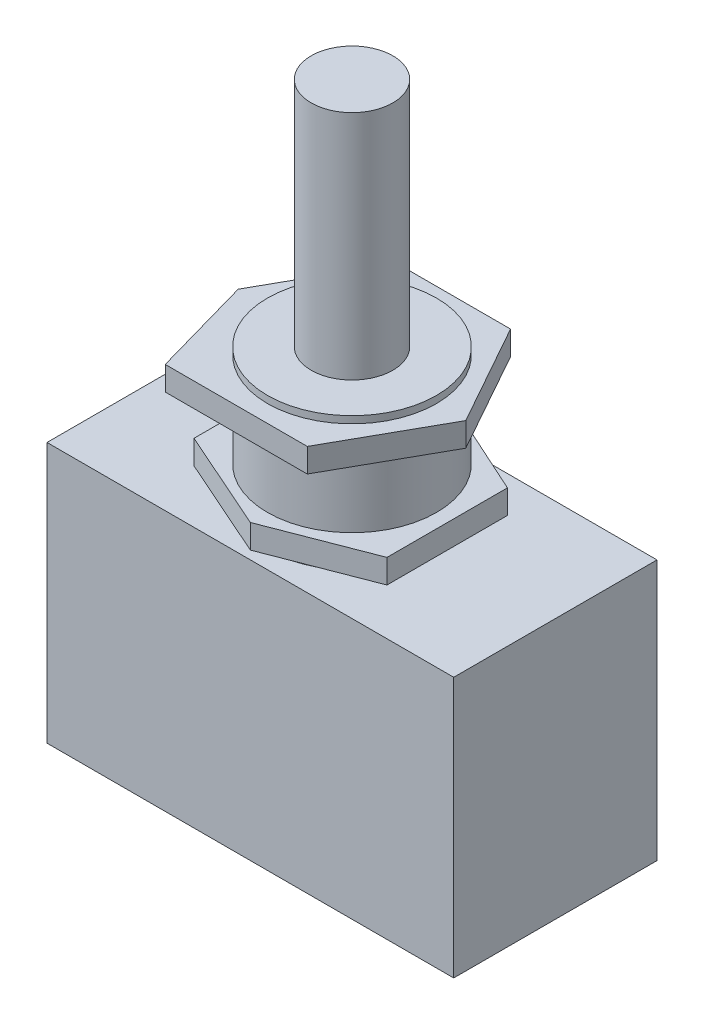
SolidWorks part; units mm, degrees
ref_plane "Front Plane" through (0, 0, 0) normal (0, 0, 1) x (1, 0, 0)
ref_plane "Top Plane" through (0, 0, 0) normal (0, 1, 0) x (1, 0, 0)
ref_plane "Right Plane" through (0, 0, 0) normal (1, 0, 0) x (0, 0, -1)
other "Configuration Table"
sketch "BodyProfile" plane through (0, 0, 0) normal (0, 0, 1) x (1, 0, 0)
  line L1 (-14.445, -9.25) -> (14.445, -9.25)
  line L2 (-14.445, -9.25) -> (-14.445, 9.25)
  line L3 (-14.445, 9.25) -> (14.445, 9.25)
  line L4 (14.445, -9.25) -> (14.445, 9.25)
  line L5 (-14.445, -9.25) -> (14.445, 9.25) construction
  line L6 (-14.445, 9.25) -> (14.445, -9.25) construction
  point P0 (0, 0)
extrude "BodyBoss" add sketch "BodyProfile" along normal mid plane 14.44
ref_plane "TopOfBodyPlane" through (0, 9.25, 0) normal (0, 1, 0) x (1, 0, 0)
ref_plane "BottomOfBodyPlane" through (0, 0, 0) normal (0, 1, 0) x (1, 0, 0)
sketch "BushingStemProfile" plane through (0, 9.25, 0) normal (0, 1, 0) x (1, 0, 0)
  circle A0 centre (0, 0) radius 6
extrude "BushingStem" add sketch "BushingStemProfile" along normal blind 9.5
sketch "WasherProfile" plane through (0, 9.25, 0) normal (0, 1, 0) x (1, 0, 0)
  circle A0 centre (0, 0) radius 6
extrude "WasherBoss" add sketch "WasherProfile" along normal blind 0.6
ref_plane "LowerNutPlane" through (0, 9.85, 0) normal (0, 1, 0) x (1, 0, 0)
sketch "LowerNutProfile" plane through (0, 9.85, 0) normal (0, 1, 0) x (1, 0, 0)
  line L0 (7, 4.0415) -> (0, 7.22)
  line L1 (14.445, 7.22) -> (-14.445, 7.22) construction
  line L2 (0, 7.22) -> (-7.1811, 4.5239)
  line L3 (-7.1811, 4.5239) -> (-7.1811, -4.0415)
  line L4 (-7.1811, -4.0415) -> (0, -7.22)
  line L5 (14.445, -7.22) -> (-14.445, -7.22) construction
  line L6 (0, -7.22) -> (7, -4.5154)
  line L7 (7, -4.5154) -> (7, 4.0415)
extrude "LowerNutBoss" add sketch "LowerNutProfile" along normal blind 1.7
ref_plane "UpperNutPlane" through (0, 11.55, 0) normal (0, 1, 0) x (1, 0, 0)
sketch "UpperNutProfile" plane through (0, 11.55, 0) normal (0, 1, 0) x (1, 0, 0)
  line L0 (8.083, 0) -> (4.0415, 7.22)
  line L1 (14.445, 7.22) -> (-14.445, 7.22) construction
  line L2 (4.0415, 7.22) -> (-4.0415, 7.22)
  line L3 (-4.0415, 7.22) -> (-8.083, 0)
  line L4 (-8.083, 0) -> (-6.0452, -7.22)
  line L5 (14.445, -7.22) -> (-14.445, -7.22) construction
  line L6 (-6.0452, -7.22) -> (4.0415, -7.22)
  line L7 (4.0415, -7.22) -> (8.083, 0)
extrude "UpperNutBoss" add sketch "UpperNutProfile" along normal blind 1.7 from offset 5
ref_plane "ActuatorBasePlane" through (0, 18.75, 0) normal (0, 1, 0) x (1, 0, 0)
sketch "ActuatorBaseProfile" plane through (0, 18.75, 0) normal (0, 1, 0) x (1, 0, 0)
  circle A0 centre (0, 0) radius 2.9
extrude "ActuatorBoss" add sketch "ActuatorBaseProfile" along normal blind 16.45
sketch "LeftTerminalProfile" plane through (0, 0, 0) normal (0, 1, 0) x (1, 0, 0)
  line L1 (-8.8, -3.1) -> (-7.2, -3.1)
  line L2 (-8.8, -3.1) -> (-8.8, 3.1)
  line L3 (-8.8, 3.1) -> (-7.2, 3.1)
  line L4 (-7.2, -3.1) -> (-7.2, 3.1)
  line L5 (-8.8, -3.1) -> (-7.2, 3.1) construction
  line L6 (-8.8, 3.1) -> (-7.2, -3.1) construction
  line L7 (7.2, -3.1) -> (8.8, -3.1)
  line L8 (7.2, -3.1) -> (7.2, 3.1)
  line L9 (7.2, 3.1) -> (8.8, 3.1)
  line L10 (8.8, -3.1) -> (8.8, 3.1)
  line L11 (7.2, -3.1) -> (8.8, 3.1) construction
  line L12 (7.2, 3.1) -> (8.8, -3.1) construction
  point P0 (-8, 0)
  point P5 (8, 0)
extrude "TerminalBosses" add sketch "LeftTerminalProfile" against normal blind 10.5
